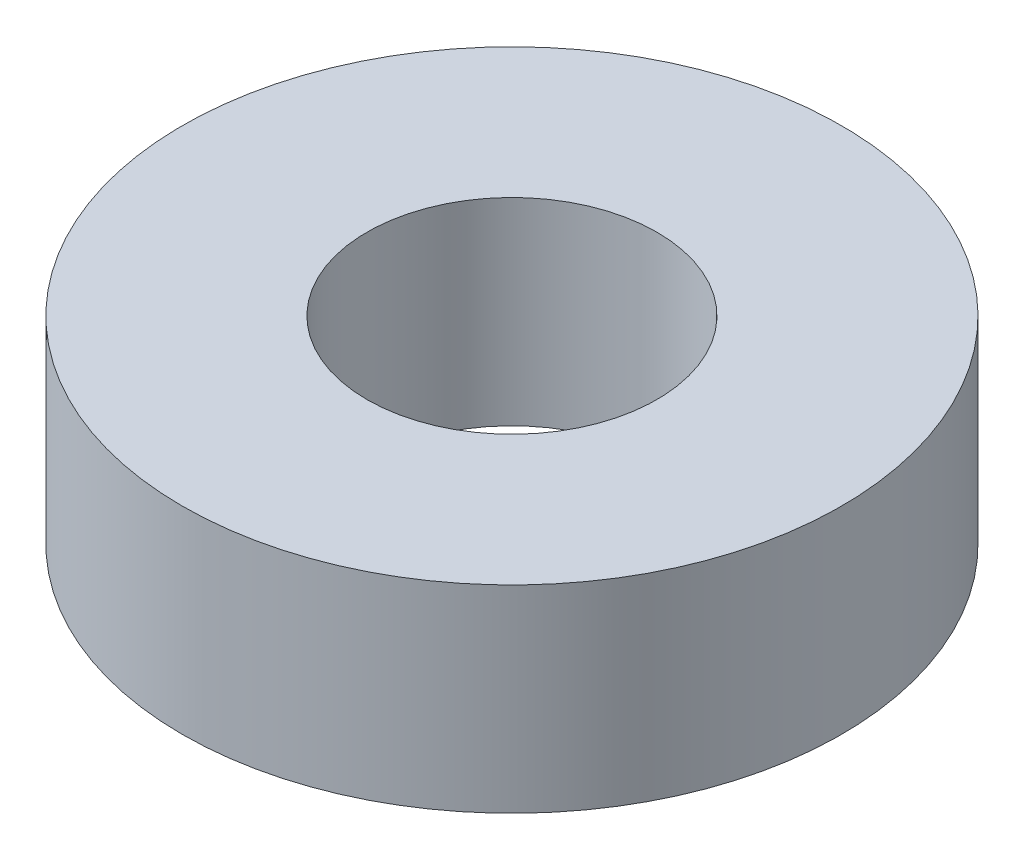
SolidWorks part; units mm, degrees
ref_plane "前视基准面" through (0, 0, 0) normal (0, 0, 1) x (1, 0, 0)
ref_plane "上视基准面" through (0, 0, 0) normal (0, 1, 0) x (1, 0, 0)
ref_plane "右视基准面" through (0, 0, 0) normal (1, 0, 0) x (0, 0, -1)
sketch "草图1" plane through (0, 0, 0) normal (0, 1, 0) x (1, 0, 0)
  circle A0 centre (0, 0) radius 1.1
  circle A1 centre (0, 0) radius 2.5
  dimension "D1" = 2.2
  dimension "D2" = 5
extrude "凸台-拉伸1" add sketch "草图1" along normal blind 1.5
